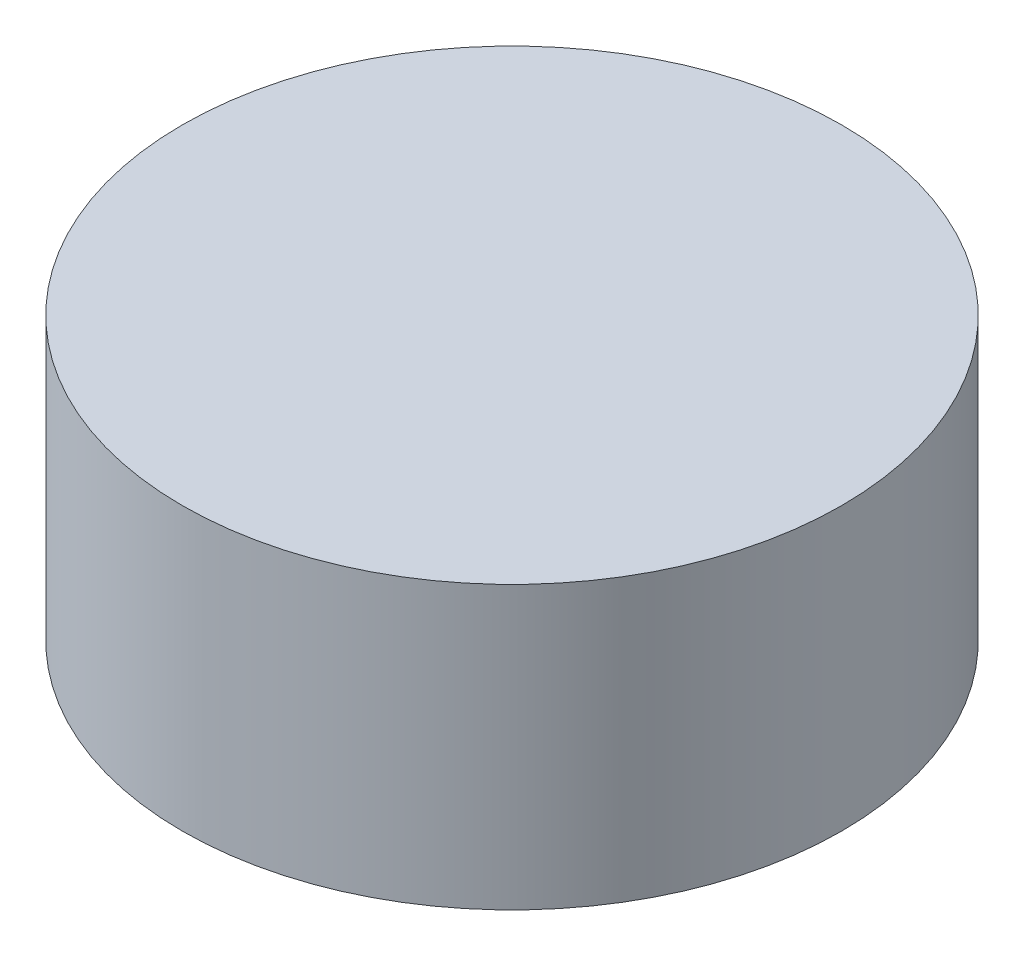
SolidWorks part; units mm, degrees
ref_plane "Front Plane" through (0, 0, 0) normal (0, 0, 1) x (1, 0, 0)
ref_plane "Top Plane" through (0, 0, 0) normal (0, 1, 0) x (1, 0, 0)
ref_plane "Right Plane" through (0, 0, 0) normal (1, 0, 0) x (0, 0, -1)
sketch "CurveSketch" plane through (0, 0, 0) normal (0, 1, 0) x (1, 0, 0)
  circle A0 centre (-7.391, 11.173) radius 13.719
  dimension "D1" = 27.438
extrude "CurveBoss" add sketch "CurveSketch" along normal blind 11.731
